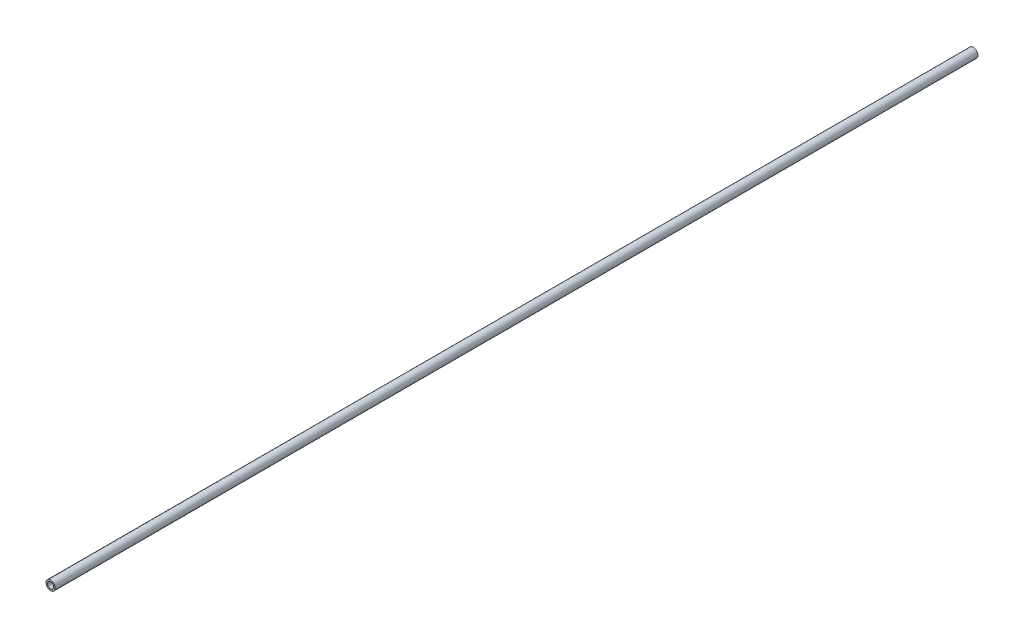
SolidWorks part; units mm, degrees
material "Tubi carbonio"
ref_plane "Piano frontale" through (0, 0, 0) normal (0, 0, 1) x (1, 0, 0)
ref_plane "Piano superiore" through (0, 0, 0) normal (0, 1, 0) x (1, 0, 0)
ref_plane "Piano destro" through (0, 0, 0) normal (1, 0, 0) x (0, 0, -1)
sketch "Schizzo1" plane through (0, 0, 0) normal (0, 0, 1) x (1, 0, 0)
  circle A0 centre (0, 0) radius 3
  circle A1 centre (0, 0) radius 2
  dimension "D1" = 4
  dimension "D2" = 6
extrude "Estrusione-Estrusione1" add sketch "Schizzo1" along normal blind 599
